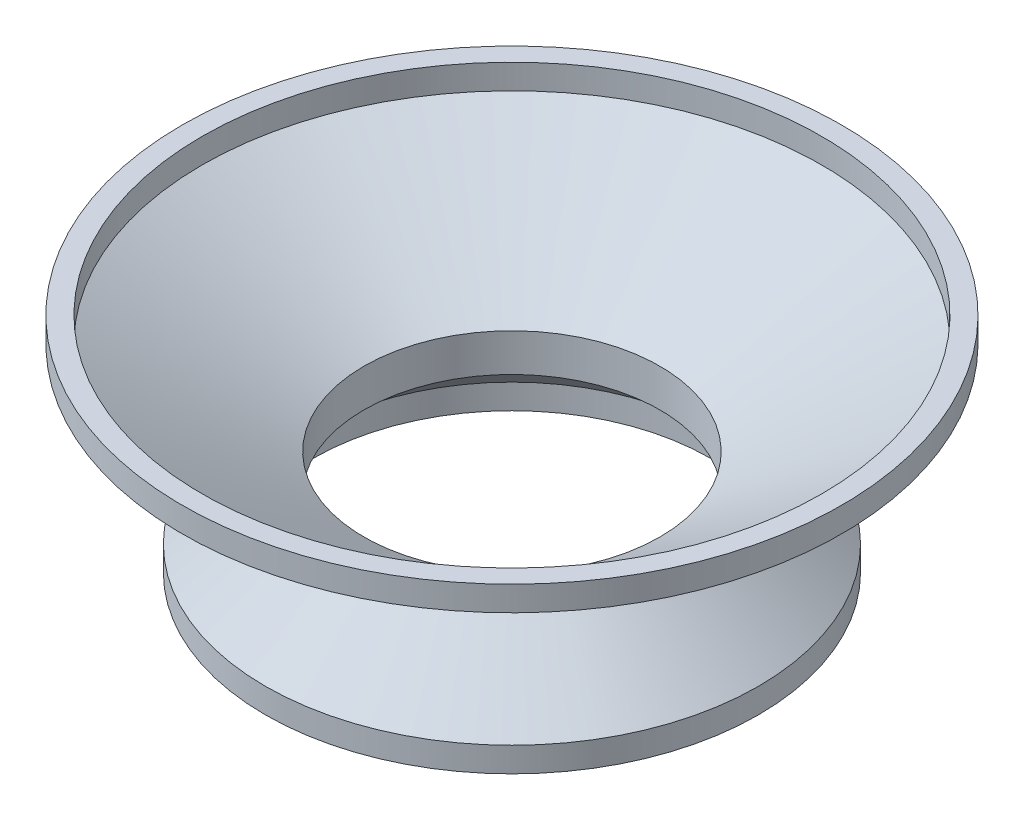
SolidWorks part; units mm, degrees
ref_plane "Front Plane" through (0, 0, 0) normal (0, 0, 1) x (1, 0, 0)
ref_plane "Top Plane" through (0, 0, 0) normal (0, 1, 0) x (1, 0, 0)
ref_plane "Right Plane" through (0, 0, 0) normal (1, 0, 0) x (0, 0, -1)
sketch "Sketch1" plane through (0, 0, 0) normal (0, 0, 1) x (1, 0, 0)
  line L0 (-42.6436, 0) -> (43.9692, 0) construction
  line L1 (0.6628, 0) -> (-13.1936, 8)
  line L2 (0.6628, 0) -> (-6.4877, -6)
  line L3 (1.4628, -2.5922) -> (-2.5984, -6)
  line L5 (-13.1936, 8) -> (-11.5936, 8)
  line L6 (-6.4877, -6) -> (-2.5984, -6)
  line L7 (13.4064, 7.609) -> (13.4064, -7.609) construction
  line L8 (5.0048, 0.3799) -> (-18.085, 13.7108) construction
  line L9 (0.6628, 0) -> (-19.335, 11.5457) construction
  line L10 (0.6628, 0) -> (-15.8334, -13.842) construction
  line L11 (5.0048, 0.3799) -> (-14.2265, -15.7571) construction
  line L12 (0.6628, 0) -> (2.2628, 0) construction
  line L13 (1.4628, -2.5922) -> (1.4628, 0.4619)
  line L14 (1.4628, 0.4619) -> (-11.5936, 8)
  point P11 (1.4628, 0)
  dimension "D1" = 30
  dimension "D2" = 40
  dimension "D4" = 8
  dimension "D5" = 6
  dimension "D6" = 25
  dimension "D7" = 1.6
  dimension "D8" = 0.8
  dimension "D3" = 2.5
revolve "Revolve1" add sketch "Sketch1" angle 360 about L7
scale "Scale1" [suppressed]
fillet "Fillet2" radius 0.4 1 edges at (0.6628, 0, 0)
sketch "Sketch2" plane through (0, 8, 0) normal (0, 1, 0) x (1, 0, 0)
  circle A0 centre (13.4064, 0) radius 26.6 construction
  circle A1 centre (13.4064, 0) radius 25 construction
  circle A2 centre (13.4064, 0) radius 26.6
  circle A3 centre (13.4064, 0) radius 25
extrude "Boss-Extrude1" add sketch "Sketch2" along normal blind 2
sketch "Sketch3" plane through (0, -6, 0) normal (0, -1, 0) x (1, 0, 0)
  circle A0 centre (13.4064, 0) radius 16.0048 construction
  circle A1 centre (13.4064, 0) radius 19.8941 construction
  circle A2 centre (13.4064, 0) radius 16.0048
  circle A3 centre (13.4064, 0) radius 19.8941
extrude "Boss-Extrude2" add sketch "Sketch3" along normal blind 2
